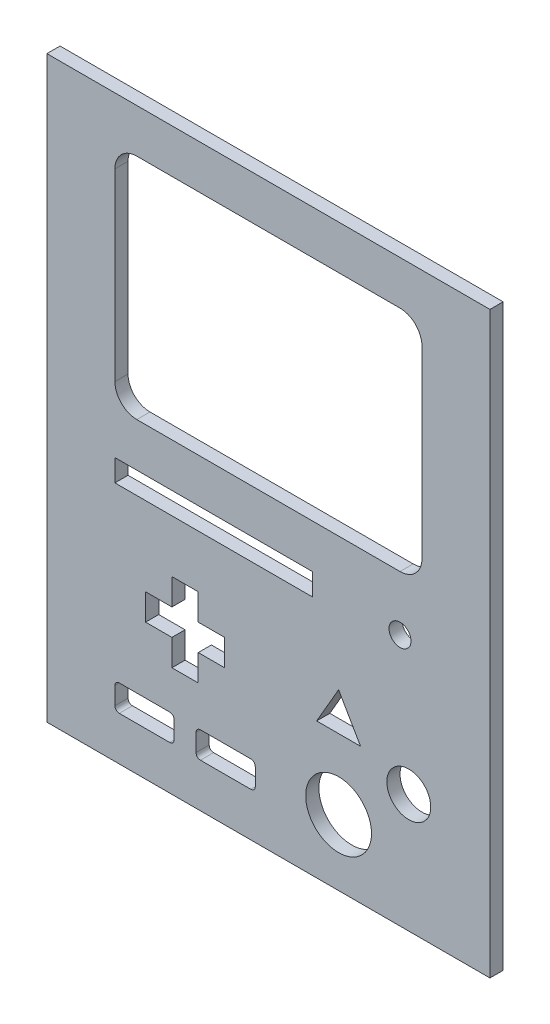
SolidWorks part; units mm, degrees
ref_plane "Front Plane" through (0, 0, 0) normal (0, 0, 1) x (1, 0, 0)
ref_plane "Top Plane" through (0, 0, 0) normal (0, 1, 0) x (1, 0, 0)
ref_plane "Right Plane" through (0, 0, 0) normal (1, 0, 0) x (0, 0, -1)
sketch "Sketch1" plane through (0, 0, 0) normal (0, 0, 1) x (1, 0, 0)
  line L1 (-50.5, -66) -> (50.5, -66)
  line L2 (-50.5, -66) -> (-50.5, 66)
  line L3 (-50.5, 66) -> (50.5, 66)
  line L4 (50.5, -66) -> (50.5, 66)
  line L5 (-50.5, -66) -> (50.5, 66) construction
  line L6 (-50.5, 66) -> (50.5, -66) construction
  point P0 (0, 0)
  dimension "D1" = 101
  dimension "D2" = 132
extrude "Boss-Extrude1" add sketch "Sketch1" along normal mid plane 3 contours L3 L4 L1 L2
sketch "Sketch2" plane through (0, 0, 1.5) normal (0, 0, 1) x (1, 0, 0)
  line L0 (-30, 4) -> (30, 4)
  line L1 (-35, 9) -> (-35, 51)
  line L2 (-30, 56) -> (30, 56)
  line L3 (35, 9) -> (35, 51)
  line L4 (-50.5, 66) -> (50.5, 66) construction
  line L5 (-50.5, -66) -> (-50.5, 66) construction
  line L6 (50.5, -66) -> (50.5, 66) construction
  line L7 (11, -35) -> (21, -35)
  line L8 (21, -35) -> (16, -26.3397)
  line L9 (16, -26.3397) -> (11, -35)
  line L10 (-50.5, -66) -> (50.5, -66) construction
  line L11 (-15.5, -56) -> (-4, -56)
  line L12 (-34, -56) -> (-22.5, -56)
  line L13 (-35, -55) -> (-35, -51)
  line L14 (-34, -50) -> (-22.5, -50)
  line L15 (-21.5, -55) -> (-21.5, -51)
  line L16 (-35, -56) -> (-21.5, -50) construction
  line L17 (-35, -50) -> (-21.5, -56) construction
  line L18 (-16.5, -55) -> (-16.5, -51)
  line L19 (-15.5, -50) -> (-4, -50)
  line L20 (-3, -55) -> (-3, -51)
  line L21 (-16.5, -56) -> (-3, -50) construction
  line L22 (-16.5, -50) -> (-3, -56) construction
  line L23 (-22, -41) -> (-16, -41)
  line L24 (-28, -35) -> (-22, -35)
  line L25 (-28, -35) -> (-28, -29)
  line L26 (-28, -29) -> (-22, -29)
  line L27 (-10, -35) -> (-10, -29)
  line L28 (-16, -29) -> (-10, -29)
  line L29 (-22, -29) -> (-22, -23)
  line L30 (-22, -41) -> (-22, -35)
  line L31 (-22, -23) -> (-16, -23)
  line L32 (-16, -41) -> (-16, -35)
  line L33 (-16, -35) -> (-10, -35)
  line L34 (-16, -29) -> (-16, -23)
  line L35 (-22, -29) -> (-16, -35) construction
  line L36 (-22, -35) -> (-16, -29) construction
  line L38 (-35, -6) -> (10, -6)
  line L39 (-35, -6) -> (-35, -11)
  line L40 (-35, -11) -> (10, -11)
  line L41 (10, -6) -> (10, -11)
  arc A0 (30, 4) -> (35, 9) centre (30, 9) ccw
  arc A1 (-30, 4) -> (-35, 9) centre (-30, 9) cw
  arc A2 (35, 51) -> (30, 56) centre (30, 51) ccw
  arc A3 (-35, 51) -> (-30, 56) centre (-30, 51) cw
  circle A4 centre (16, -51) radius 7.5
  circle A5 centre (32, -39) radius 5
  arc A6 (-21.5, -51) -> (-22.5, -50) centre (-22.5, -51) ccw
  arc A7 (-22.5, -56) -> (-21.5, -55) centre (-22.5, -55) ccw
  arc A8 (-35, -55) -> (-34, -56) centre (-34, -55) ccw
  arc A9 (-35, -51) -> (-34, -50) centre (-34, -51) cw
  arc A10 (-3, -51) -> (-4, -50) centre (-4, -51) ccw
  arc A11 (-4, -56) -> (-3, -55) centre (-4, -55) ccw
  arc A12 (-16.5, -55) -> (-15.5, -56) centre (-15.5, -55) ccw
  arc A13 (-16.5, -51) -> (-15.5, -50) centre (-15.5, -51) cw
  circle A14 centre (30, -8.5) radius 2.5
  point P14 (-35, 4)
  point P19 (-35, 56)
  point P30 (-28.25, -53)
  point P47 (-9.75, -53)
  point P63 (-19, -32)
  point P68 (-19, -32)
  dimension "D5" = 5
  dimension "D6" = 0
  dimension "D9" = 10
  dimension "D10" = 15
  dimension "D13" = 12
  dimension "D15" = 62
  dimension "D17" = 1
  dimension "D20" = 1
  dimension "D36" = 5
  dimension "D1" = 10
  dimension "D2" = 15.5
  dimension "D3" = 15.5
  dimension "D4" = 52
  dimension "D7" = 16
  dimension "D8" = 16
  dimension "D11" = 10
  dimension "D12" = 13.5
  dimension "D14" = 15
  dimension "D16" = 6
  dimension "D18" = 62
  dimension "D19" = 0
  dimension "D21" = 5
  dimension "D22" = 0
  dimension "D23" = 13.5
  dimension "D24" = 6
  dimension "D25" = 18
  dimension "D26" = 6
  dimension "D27" = 6
  dimension "D28" = 18
  dimension "D29" = 2.5
  dimension "D30" = 18
  dimension "D31" = 6
  dimension "D32" = 6
  dimension "D33" = 5
  dimension "D34" = 45
  dimension "D35" = 10
  dimension "D37" = 20
  dimension "D38" = 2.5
  dimension "D39" = 70
extrude "Cut-Extrude2" cut sketch "Sketch2" against normal through all
